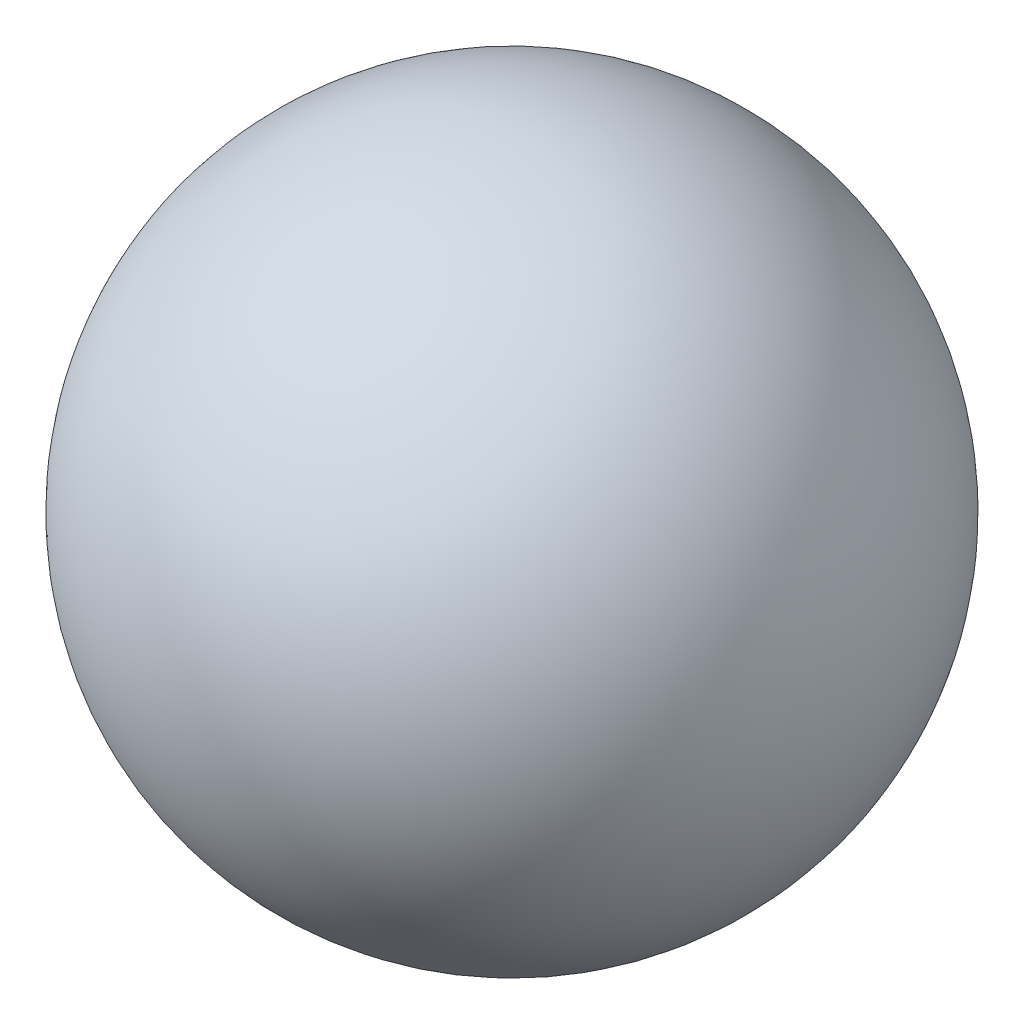
SolidWorks part; units mm, degrees
ref_plane "Front Plane" through (0, 0, 0) normal (0, 0, 1) x (1, 0, 0)
ref_plane "Top Plane" through (0, 0, 0) normal (0, 1, 0) x (1, 0, 0)
ref_plane "Right Plane" through (0, 0, 0) normal (1, 0, 0) x (0, 0, -1)
sketch "Sketch2" plane through (0, 0, 0) normal (0, 0, 1) x (1, 0, 0)
  line L0 (-12, 0) -> (12, 0) construction
  line L1 (-12, 0) -> (12, 0)
  arc A0 (-12, 0) -> (12, 0) centre (0, 0) ccw
  dimension "D1" = 12
  dimension "D2" = 24
revolve "Revolve1" add sketch "Sketch2" angle 360 about L0
